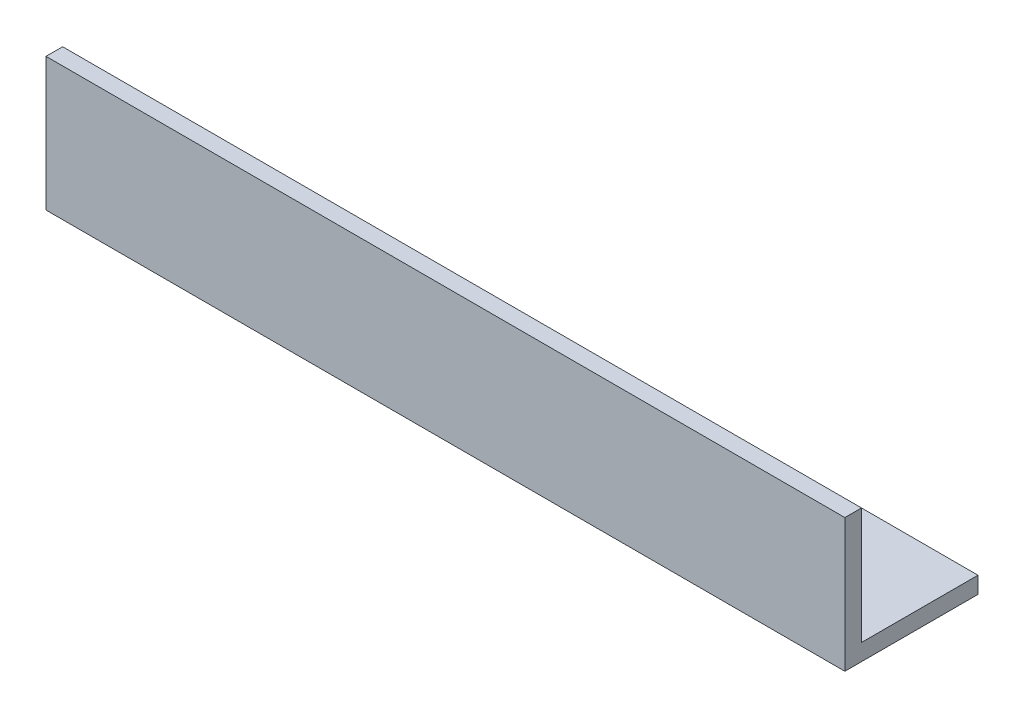
SolidWorks part; units mm, degrees
ref_plane "Front Plane" through (0, 0, 0) normal (0, 0, 1) x (1, 0, 0)
ref_plane "Top Plane" through (0, 0, 0) normal (0, 1, 0) x (1, 0, 0)
ref_plane "Right Plane" through (0, 0, 0) normal (1, 0, 0) x (0, 0, -1)
sketch "Sketch1" plane through (0, 0, 0) normal (1, 0, 0) x (0, 0, -1)
  line L0 (0, 0) -> (50.8, 0)
  line L1 (0, 0) -> (0, 50.8)
  line L2 (0, 50.8) -> (6.35, 50.8)
  line L3 (6.35, 50.8) -> (6.35, 6.35)
  line L4 (6.35, 6.35) -> (50.8, 6.35)
  line L5 (50.8, 6.35) -> (50.8, 0)
  dimension "D1" = 50.8
  dimension "D2" = 50.8
  dimension "D3" = 6.35
  dimension "D4" = 6.35
extrude "Boss-Extrude1" add sketch "Sketch1" along normal blind 304.8
sketch "Sketch2" plane through (0, 6.35, 0) normal (0, 1, 0) x (1, 0, 0)
  line L0 (152.4, 50.8) -> (152.4, 0) construction
  line L1 (304.8, 50.8) -> (0, 50.8) construction
  line L2 (304.8, 0) -> (0, 0) construction
  line L3 (50.8, 42.8625) -> (50.8, 17.4625) construction
  line L4 (53.975, 42.8625) -> (53.975, 17.4625)
  line L5 (47.625, 42.8625) -> (47.625, 17.4625)
  line L6 (254, 42.8625) -> (254, 17.4625) construction
  line L7 (250.825, 42.8625) -> (250.825, 17.4625)
  line L8 (257.175, 42.8625) -> (257.175, 17.4625)
  arc A0 (53.975, 42.8625) -> (47.625, 42.8625) centre (50.8, 42.8625) ccw
  arc A1 (47.625, 17.4625) -> (53.975, 17.4625) centre (50.8, 17.4625) ccw
  arc A2 (250.825, 42.8625) -> (257.175, 42.8625) centre (254, 42.8625) cw
  arc A3 (257.175, 17.4625) -> (250.825, 17.4625) centre (254, 17.4625) cw
  point P8 (50.8, 30.1625)
  point P15 (254, 30.1625)
  dimension "D1" = 6.35
  dimension "D2" = 25.4
  dimension "D3" = 7.9375
  dimension "D4" = 101.6
extrude "Cut-Extrude1" cut sketch "Sketch2" against normal through all
